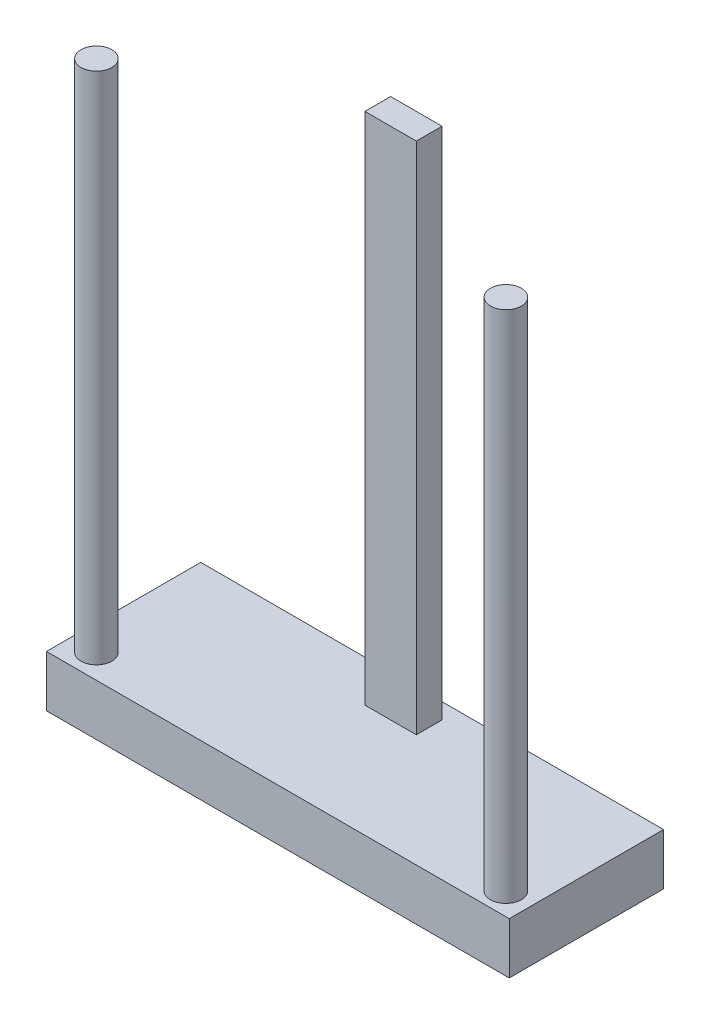
SolidWorks part; units mm, degrees
ref_plane "Front Plane" through (0, 0, 0) normal (0, 0, 1) x (1, 0, 0)
ref_plane "Top Plane" through (0, 0, 0) normal (0, 1, 0) x (1, 0, 0)
ref_plane "Right Plane" through (0, 0, 0) normal (1, 0, 0) x (0, 0, -1)
sketch "Sketch1" plane through (0, 0, 0) normal (0, 1, 0) x (1, 0, 0)
  line L1 (-114.3, -11.9666) -> (114.3, -11.9666)
  line L2 (-114.3, -11.9666) -> (-114.3, 64.2334)
  line L3 (-114.3, 64.2334) -> (114.3, 64.2334)
  line L4 (114.3, -11.9666) -> (114.3, 64.2334)
  dimension "D1" = 228.6
  dimension "D2" = 76.2
  dimension "D3" = 114.3
extrude "Boss-Extrude1" add sketch "Sketch1" along normal blind 25.4
sketch "Sketch2" plane through (0, 25.4, 0) normal (0, 1, 0) x (1, 0, 0)
  line L1 (-12.7, 43.7189) -> (12.7, 43.7189)
  line L2 (-12.7, 43.7189) -> (-12.7, 56.4189)
  line L3 (-12.7, 56.4189) -> (12.7, 56.4189)
  line L4 (12.7, 43.7189) -> (12.7, 56.4189)
  circle A0 centre (-101.6, 0) radius 7.62
  circle A1 centre (101.6, -0.9156) radius 7.62
  dimension "D1" = 203.2
  dimension "D2" = 101.6
  dimension "D3" = 25.4
  dimension "D4" = 12.7
  dimension "D5" = 12.7
  dimension "D6" = 56.4189
extrude "Boss-Extrude2" add sketch "Sketch2" along normal blind 254
